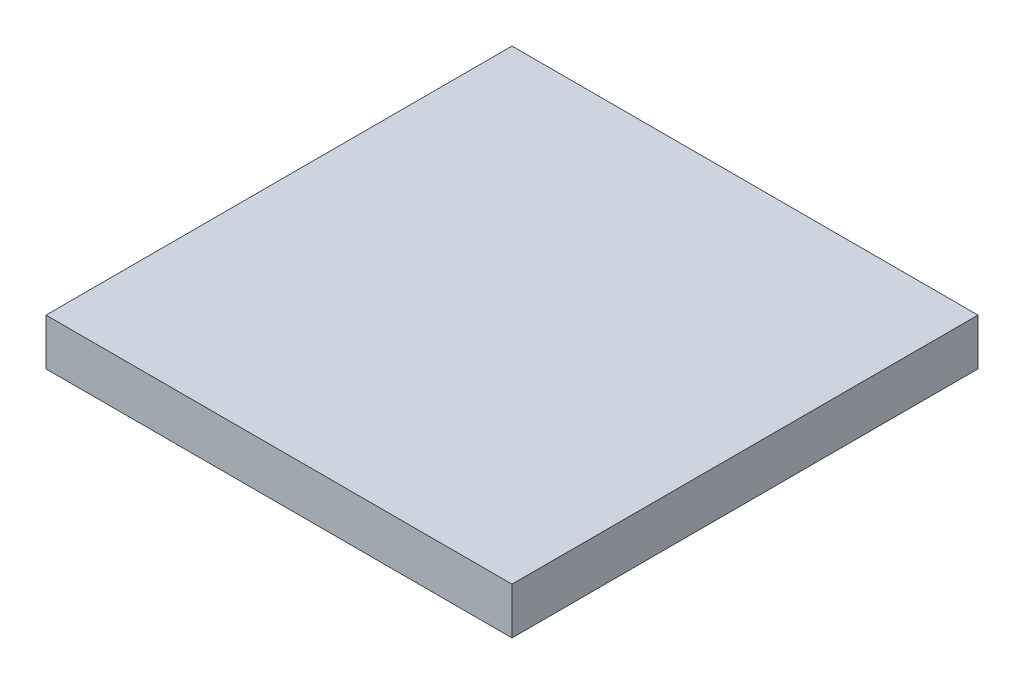
SolidWorks part; units mm, degrees
ref_plane "前视基准面" through (0, 0, 0) normal (0, 0, 1) x (1, 0, 0)
ref_plane "上视基准面" through (0, 0, 0) normal (0, 1, 0) x (1, 0, 0)
ref_plane "右视基准面" through (0, 0, 0) normal (1, 0, 0) x (0, 0, -1)
other "Configuration Table"
sketch "草图1" plane through (0, 0, 0) normal (0, 1, 0) x (1, 0, 0)
  line L1 (-12.5, 12.5) -> (12.5, 12.5)
  line L2 (-12.5, 12.5) -> (-12.5, -12.5)
  line L3 (-12.5, -12.5) -> (12.5, -12.5)
  line L4 (12.5, 12.5) -> (12.5, -12.5)
  line L5 (-12.5, 12.5) -> (12.5, -12.5) construction
  line L6 (-12.5, -12.5) -> (12.5, 12.5) construction
  point P0 (0, 0)
  dimension "D1" = 25
  dimension "D2" = 25
extrude "凸台-拉伸1" add sketch "草图1" against normal blind 2.5
